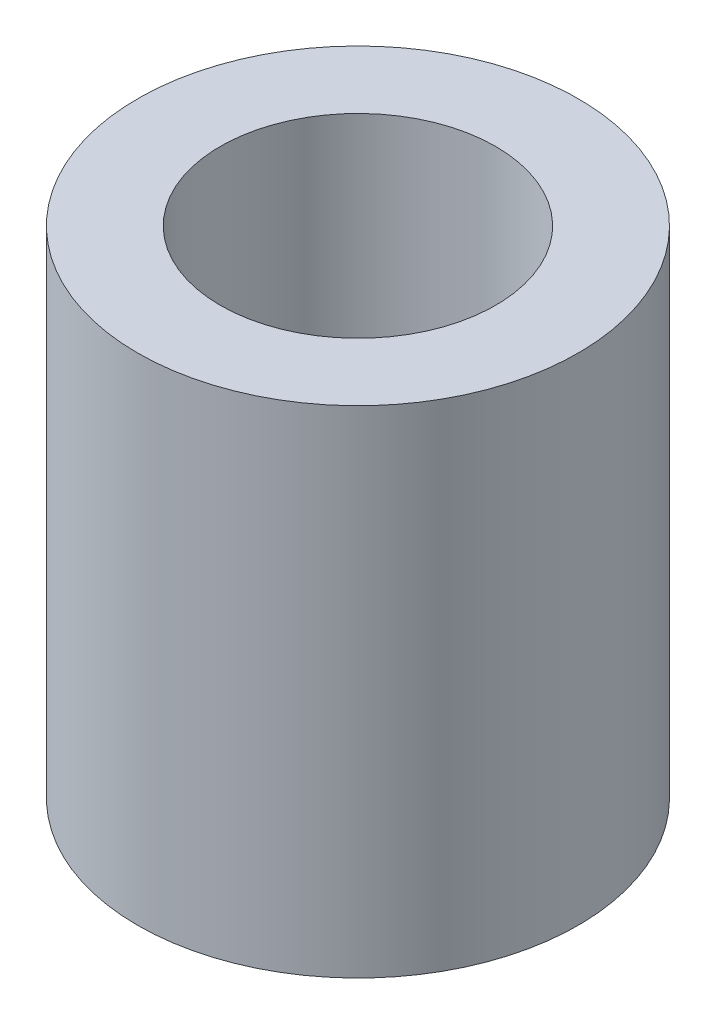
SolidWorks part; units mm, degrees
ref_plane "Front Plane" through (0, 0, 0) normal (0, 0, 1) x (1, 0, 0)
ref_plane "Top Plane" through (0, 0, 0) normal (0, 1, 0) x (1, 0, 0)
ref_plane "Right Plane" through (0, 0, 0) normal (1, 0, 0) x (0, 0, -1)
sketch "Sketch1" plane through (0, 0, 0) normal (0, 1, 0) x (1, 0, 0)
  circle A0 centre (0, 0) radius 2.5
  circle A1 centre (0, 0) radius 4
  dimension "D1" = 8
  dimension "D2" = 5
extrude "Boss-Extrude1" add sketch "Sketch1" along normal blind 9
